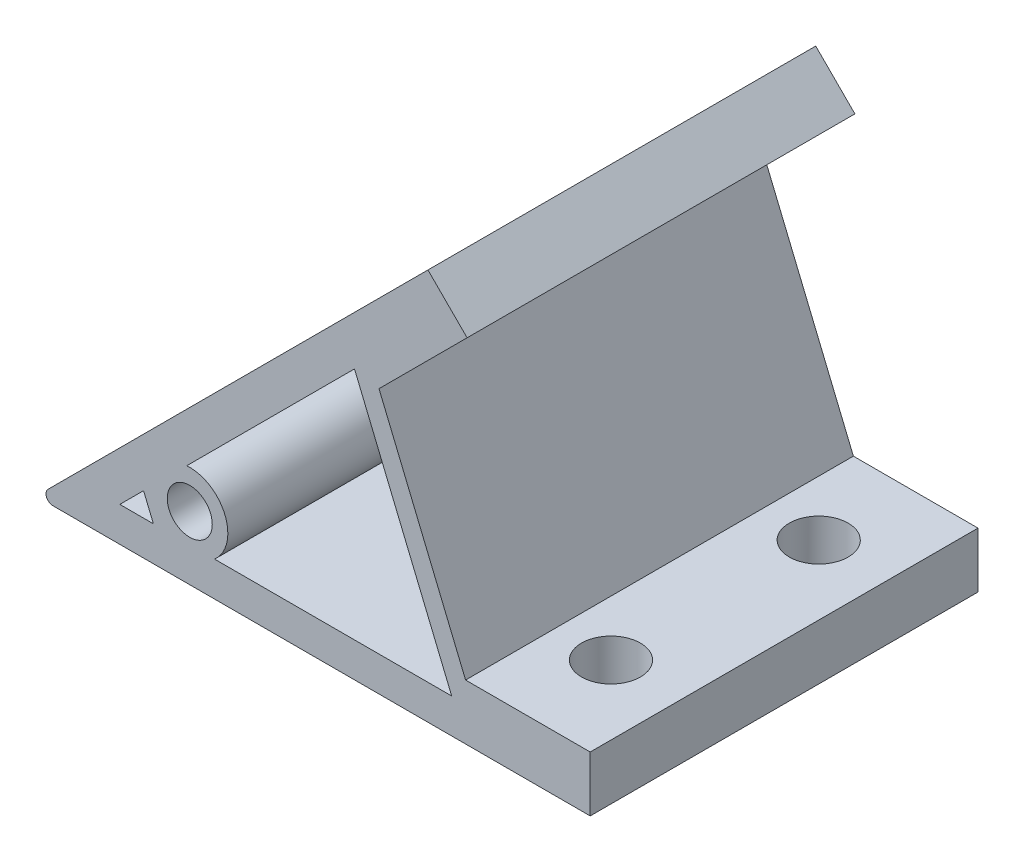
SolidWorks part; units mm, degrees
ref_plane "前视基准面" through (0, 0, 0) normal (0, 0, 1) x (1, 0, 0)
ref_plane "上视基准面" through (0, 0, 0) normal (0, 1, 0) x (1, 0, 0)
ref_plane "右视基准面" through (0, 0, 0) normal (1, 0, 0) x (0, 0, -1)
sketch "草图1" plane through (0, 0, 0) normal (0, 0, 1) x (1, 0, 0)
  line B0 (-77.5858, 0) -> (0, 0)
  line B1 (-67.9289, 5) -> (-63.0745, 5)
  line B2 (-54.2575, 5) -> (-20, 5)
  line B3 (-17.9955, 8) -> (0, 8)
  line B4 (-78.2929, 1.7071) -> (-23.4315, 56.5685)
  line B5 (-67.9289, 5) -> (-64.4963, 8.4326)
  line B6 (-58.2617, 14.6672) -> (-34.0381, 38.8909)
  line B7 (-30.4993, 38.187) -> (-17.7746, 50.9117)
  line B8 (0, 0) -> (0, 8)
  line B9 (-17.7746, 50.9117) -> (-23.4315, 56.5685)
  line B10 (-20, 5) -> (-34.0381, 38.8909)
  line B11 (-17.9955, 8) -> (-30.4993, 38.187)
  line B12 (-63.0745, 5) -> (-64.4963, 8.4326)
  arc B13 (-78.2929, 1.7071) -> (-77.5858, 0) centre (-77.5858, 1) ccw
  circle B14 centre (-57.8269, 9.1844) radius 3.25
  arc B15 (-54.2575, 5) -> (-58.2617, 14.6672) centre (-57.8269, 9.1844) ccw
sketch_block_instance "A$C18907C9D-1"
sketch_block "A$C18907C9D"
extrude "凸台-拉伸1" add sketch "草图1" along normal mid plane 56
sketch "草图3" plane through (0, 8, 0) normal (0, 1, 0) x (1, 0, 0)
  line L0 (0, -28) -> (0, 28) construction
  line L1 (0, -28) -> (-17.9955, -28) construction
  line L2 (0, 0) -> (-16.9231, 0) construction
  circle A0 centre (-10, -15) radius 4.25
  circle A1 centre (-10, 15) radius 4.25
  dimension "D1" = 10
  dimension "D2" = 13
extrude "切除-拉伸1" cut sketch "草图3" against normal blind 17
sketch "草图4" plane through (-12.5317, -5.1908, 0) normal (0.9239, 0.3827, 0) x (0, 0, -1)
  line L0 (-28, 30.6147) -> (28, 30.6147) construction
  line L1 (-28, 14.2776) -> (-28, 46.9517) construction
  line L2 (28, 14.2776) -> (28, 46.9517) construction
ref_plane "基准面2" through (-11.7157, 28.2843, 0) normal (-0.3827, 0.9239, 0) x (0.9239, 0.3827, 0)
mirror "镜向1" about plane through (-11.7157, 28.2843, 0) normal (-0.3827, 0.9239, 0) of "切除-拉伸1"
